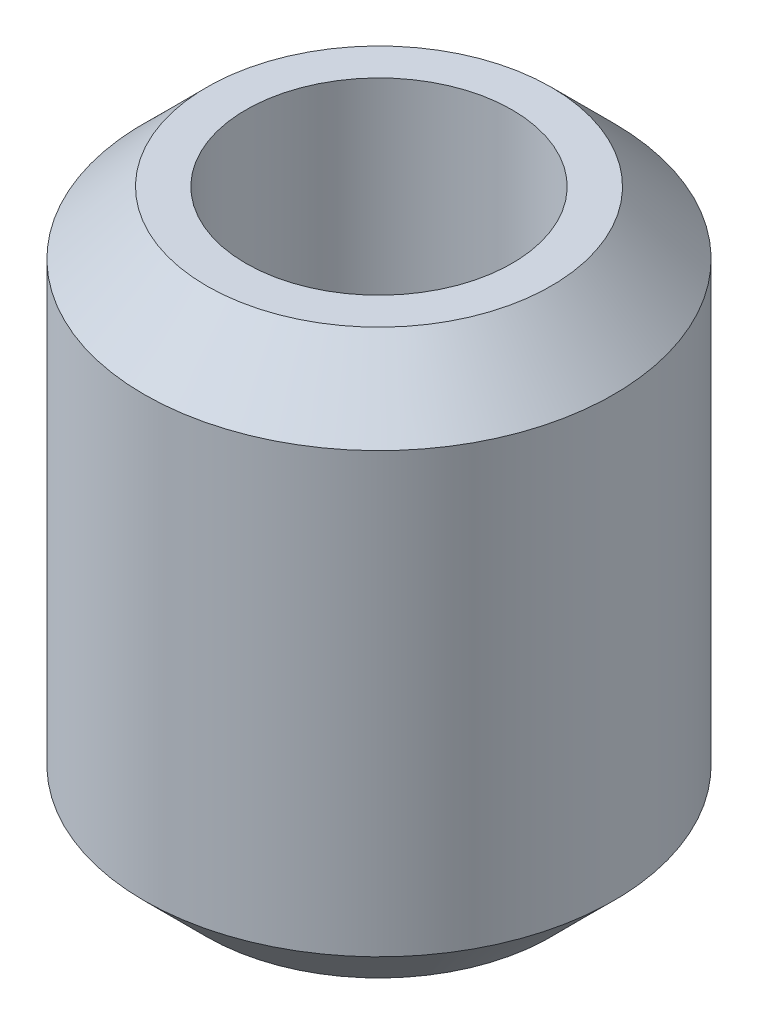
SolidWorks part; units mm, degrees
ref_plane "Спереди" through (0, 0, 0) normal (0, 0, 1) x (1, 0, 0)
ref_plane "Сверху" through (0, 0, 0) normal (0, 1, 0) x (1, 0, 0)
ref_plane "Справа" through (0, 0, 0) normal (1, 0, 0) x (0, 0, -1)
sketch "Эскиз1" plane through (0, 0, 0) normal (0, 1, 0) x (1, 0, 0)
  circle A0 centre (0, 0) radius 4.25
  circle A1 centre (0, 0) radius 7.5
  dimension "D1" = 8.5
  dimension "D2" = 15
extrude "Бобышка-Вытянуть1" add sketch "Эскиз1" along normal blind 18
chamfer "Фаска1" distance 2 angle 45 2 edges at (0, 18, 7.5) (0, 0, 7.5)
